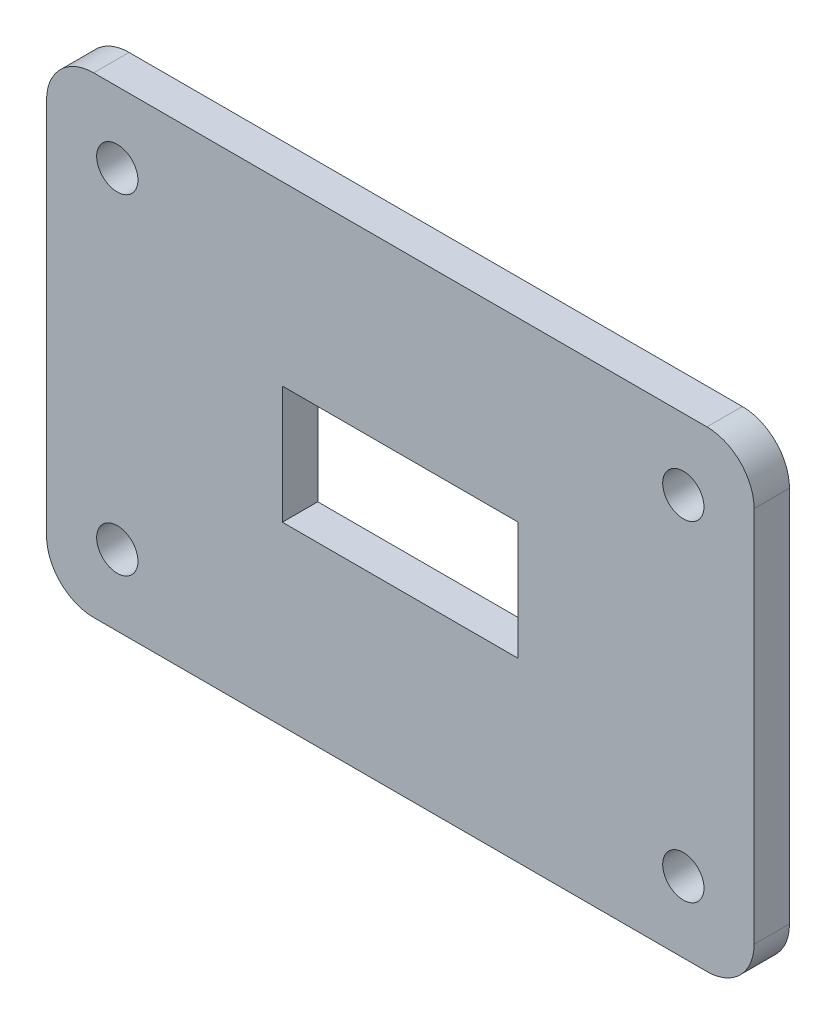
SolidWorks part; units mm, degrees
ref_plane "前视基准面" through (0, 0, 0) normal (0, 0, 1) x (1, 0, 0)
ref_plane "上视基准面" through (0, 0, 0) normal (0, 1, 0) x (1, 0, 0)
ref_plane "右视基准面" through (0, 0, 0) normal (1, 0, 0) x (0, 0, -1)
sketch "草图1" plane through (0, 0, 0) normal (0, 0, 1) x (1, 0, 0)
  line L0 (-52, -40) -> (52, -40)
  line L1 (60, -32) -> (60, 32)
  line L2 (52, 40) -> (-52, 40)
  line L3 (-60, 32) -> (-60, -32)
  arc A0 (-60, -32) -> (-52, -40) centre (-52, -32) ccw
  arc A1 (52, -40) -> (60, -32) centre (52, -32) ccw
  arc A2 (60, 32) -> (52, 40) centre (52, 32) ccw
  arc A3 (-52, 40) -> (-60, 32) centre (-52, 32) ccw
extrude "凸台-拉伸1" add sketch "草图1" along normal blind 6
sketch "草图2" plane through (0, 0, 0) normal (0, 0, 1) x (1, 0, 0)
  circle A0 centre (-48, -28) radius 3.5
  circle A1 centre (-48, 28) radius 3.5
  circle A2 centre (48, -28) radius 3.5
  circle A3 centre (48, 28) radius 3.5
extrude "切除-拉伸1" cut sketch "草图2" along normal through all
sketch "草图3" plane through (0, 0, 0) normal (0, 0, 1) x (1, 0, 0)
  line L0 (-20, -10) -> (20, -10)
  line L1 (20, -10) -> (20, 10)
  line L2 (20, 10) -> (-20, 10)
  line L3 (-20, 10) -> (-20, -10)
extrude "切除-拉伸2" cut sketch "草图3" against normal mid plane 242
